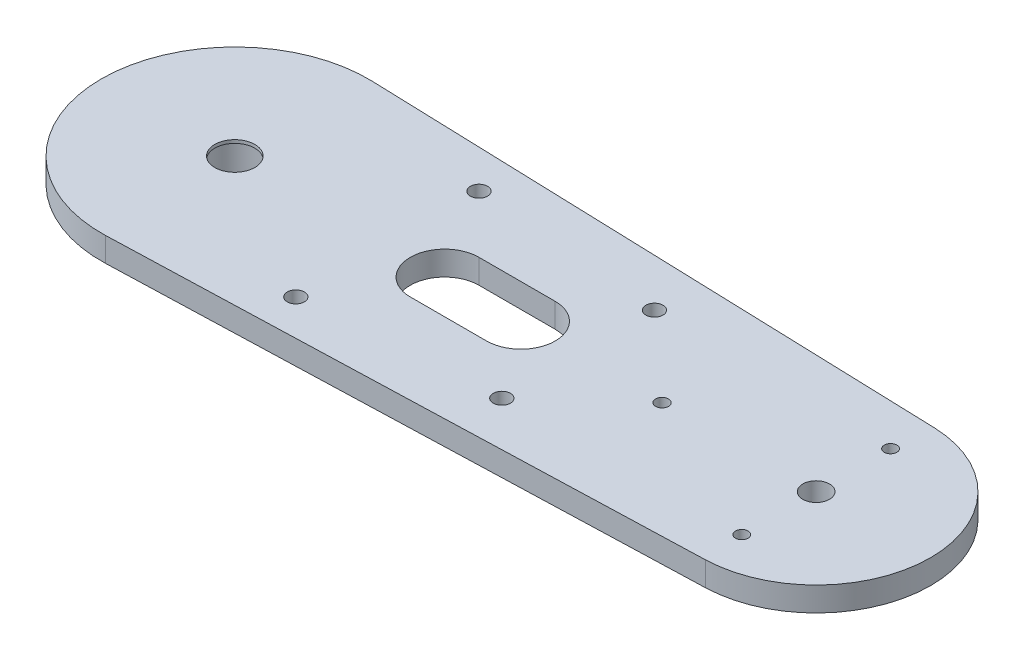
SolidWorks part; units mm, degrees
material "Aleación 6061"
ref_plane "Alzado" through (0, 0, 0) normal (0, 0, 1) x (1, 0, 0)
ref_plane "Planta" through (0, 0, 0) normal (0, 1, 0) x (1, 0, 0)
ref_plane "Vista lateral" through (0, 0, 0) normal (1, 0, 0) x (0, 0, -1)
sketch "Croquis1" plane through (0, 0, 0) normal (0, 1, 0) x (1, 0, 0)
  line L0 (1.1483, -206.4312) -> (153.3843, -201.4338)
  line L1 (153.3843, -201.4338) -> (153.3843, -141.4662)
  line L2 (153.3843, -141.4662) -> (1.1483, -136.4688)
  line L3 (1.1483, -136.4688) -> (1.1483, -206.4312)
  dimension "D1" = 1.1483
  dimension "D2" = 206.4312
  dimension "D3" = 153.3843
  dimension "D4" = 201.4338
  dimension "D5" = 153.3843
  dimension "D6" = 141.4662
  dimension "D7" = 1.1483
  dimension "D8" = 136.4688
extrude "Placa" add sketch "Croquis1" along normal blind 6.35 from offset 10.35
sketch "Croquis2" plane through (0, 0, 0) normal (0, 1, 0) x (1, 0, 0)
  circle A0 centre (0, -171.45) radius 35
  dimension "D1" = 70
  dimension "D2" = 171.45
extrude "Placa_r1" add sketch "Croquis2" along normal blind 6.35 from offset 10.35
sketch "Croquis3" plane through (0, 0, 0) normal (0, 1, 0) x (1, 0, 0)
  circle A0 centre (152.4, -171.45) radius 30
  dimension "D1" = 60
  dimension "D2" = 152.4
  dimension "D3" = 171.45
extrude "Placa_r2" add sketch "Croquis3" along normal blind 6.35 from offset 10.35
sketch "Croquis4" plane through (0, 0, 0) normal (0, 1, 0) x (1, 0, 0)
  line L0 (55, -162.45) -> (75, -162.45)
  line L1 (75, -180.45) -> (55, -180.45)
  arc A0 (75, -162.45) -> (75, -180.45) centre (75, -171.45) cw
  arc A1 (55, -180.45) -> (55, -162.45) centre (55, -171.45) cw
  dimension "D1" = 9
  dimension "D2" = 9
  dimension "D3" = 55
  dimension "D4" = 162.45
  dimension "D5" = 75
  dimension "D6" = 162.45
  dimension "D7" = 75
  dimension "D8" = 180.45
  dimension "D9" = 55
  dimension "D10" = 180.45
extrude "Aligerado" cut sketch "Croquis4" along normal blind 6.35 from offset 10.35
sketch "Croquis5" plane through (0, 0, 0) normal (0, 1, 0) x (1, 0, 0)
  circle A0 centre (40, -195.45) radius 2.25
  circle A1 centre (40, -147.45) radius 2.25
  circle A2 centre (90, -191.45) radius 2.25
  circle A3 centre (90, -151.45) radius 2.25
  dimension "D1" = 4.5
  dimension "D2" = 4.5
  dimension "D3" = 4.5
  dimension "D4" = 4.5
  dimension "D5" = 40
  dimension "D6" = 195.45
  dimension "D7" = 40
  dimension "D8" = 147.45
  dimension "D9" = 90
  dimension "D10" = 191.45
  dimension "D11" = 90
  dimension "D12" = 151.45
extrude "Barrenos_separadores_M4" cut sketch "Croquis5" along normal blind 6.35 from offset 10.35
sketch "Croquis6" plane through (0, 0, 0) normal (0, 1, 0) x (1, 0, 0)
  circle A0 centre (0, -171.45) radius 5.25
  circle A1 centre (152.4, -171.45) radius 3.5
  circle A2 centre (152.4, -190.95) radius 1.65
  circle A3 centre (152.4, -151.95) radius 1.65
  dimension "D1" = 10.5
  dimension "D2" = 7
  dimension "D3" = 3.3
  dimension "D4" = 3.3
  dimension "D5" = 171.45
  dimension "D6" = 152.4
  dimension "D7" = 171.45
  dimension "D8" = 152.4
  dimension "D9" = 190.95
  dimension "D10" = 152.4
  dimension "D11" = 151.95
extrude "Paso_pin_y_rosca_M4_ejefalso" cut sketch "Croquis6" along normal blind 6.35 from offset 10.35
sketch "Croquis7" plane through (0, 0, 0) normal (0, 1, 0) x (1, 0, 0)
  circle A0 centre (112, -171.45) radius 1.25
  dimension "D1" = 2.5
  dimension "D2" = 112
  dimension "D3" = 171.45
extrude "Rosca_M3_bases_cincho" cut sketch "Croquis7" along normal blind 6.35 from offset 10.35
sketch "Croquis8" plane through (0, 0, 0) normal (0, 1, 0) x (1, 0, 0)
  circle A0 centre (112, -171.45) radius 1.7
  dimension "D1" = 3.4
  dimension "D2" = 112
  dimension "D3" = 171.45
extrude "Paso_M3_bases_cincho" cut sketch "Croquis8" along normal blind 6.35 from offset 10.35
sketch "Croquis9" plane through (0, -10.35, 0) normal (0, -1, 0) x (1, 0, 0)
  circle A0 centre (0, 171.45) radius 10
extrude "Saliente-Extruir1" add sketch "Croquis9" along normal blind 4.5
sketch "Croquis10" plane through (0, -14.85, 0) normal (0, -1, 0) x (1, 0, 0)
  circle A0 centre (0, 171.45) radius 7.475
  dimension "D1" = 14.95
extrude "Cortar-Extruir1" cut sketch "Croquis10" against normal blind 10
